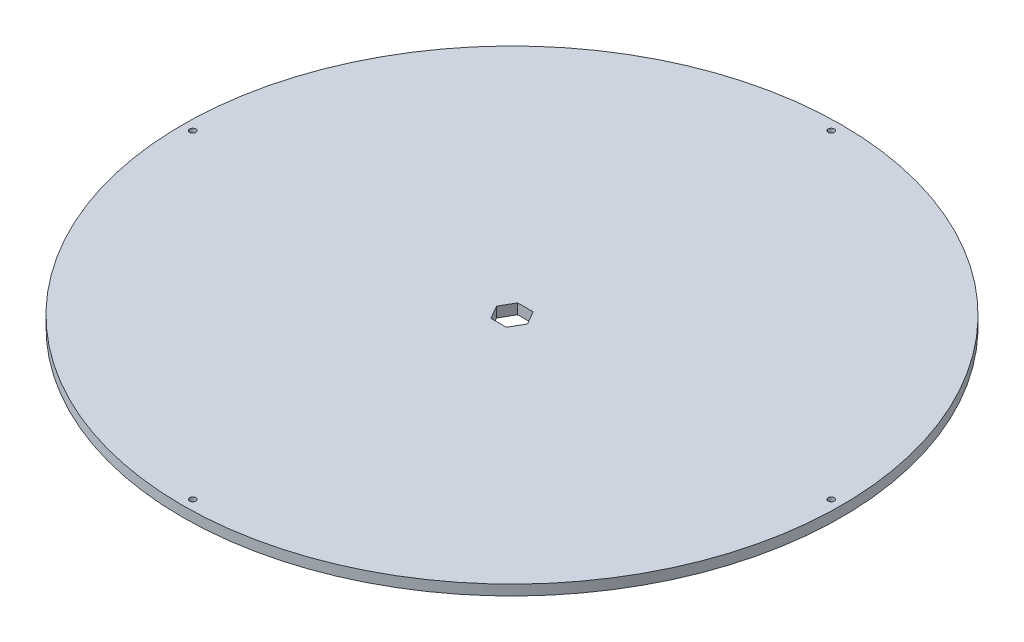
SolidWorks part; units mm, degrees
material "Pine"
ref_plane "Front Plane" through (0, 0, 0) normal (0, 0, 1) x (1, 0, 0)
ref_plane "Top Plane" through (0, 0, 0) normal (0, 1, 0) x (1, 0, 0)
ref_plane "Right Plane" through (0, 0, 0) normal (1, 0, 0) x (0, 0, -1)
sketch "Sketch1" plane through (0, 0, 0) normal (0, 1, 0) x (1, 0, 0)
  line L0 (0, 0) -> (197.1788, 0) construction
  line L2 (7.5056, 0) -> (3.7528, 6.5)
  line L3 (3.7528, 6.5) -> (-3.7528, 6.5)
  line L4 (-3.7528, 6.5) -> (-7.5056, 0)
  line L5 (-7.5056, 0) -> (-3.7528, -6.5)
  line L6 (-3.7528, -6.5) -> (3.7528, -6.5)
  line L7 (3.7528, -6.5) -> (7.5056, 0)
  circle A0 centre (0, 0) radius 160
  circle A1 centre (155, 0) radius 1.5
  circle A2 centre (0, -155) radius 1.5
  circle A3 centre (-155, 0) radius 1.5
  circle A4 centre (0, 155) radius 1.5
  circle A5 centre (0, 0) radius 6.5 construction
  point P16 (0, 0)
  dimension "D1" = 320
  dimension "D2" = 3
  dimension "D5" = 13
  dimension "D3" = 155
  dimension "D4" = 4
extrude "Boss-Extrude1" add sketch "Sketch1" against normal blind 5
equation "\"rod_diameter\"= 8"
equation "\"rod_hole_thickness\"= 4"
equation "\"rod_radius\"= \"rod_diameter\" / 2"
equation "\"platter_diameter\"= 320"
equation "\"platter_radius\"= \"platter_diameter\" / 2"
equation "\"extruder_mount_hole_spacing\"= 75"
equation "\"arm_rod_spacing\"= 40"
equation "\"motor_level_rod_spacing\"= 15"
equation "\"linear_bearing_diameter\"= 15"
equation "\"z_rod_spacing\"= 75"
equation "\"platter_rod_spacing\"= 50"
equation "\"rod_nut_thickness\"= 6.5"
equation "\"rod_nut_inscribed_diameter\"= 13"
equation "\"z_height\"= 350"
equation "\"D1@Sketch1\"=\"platter_diameter\""
equation "\"D3@Sketch1\"=\"platter_radius\"-5"
